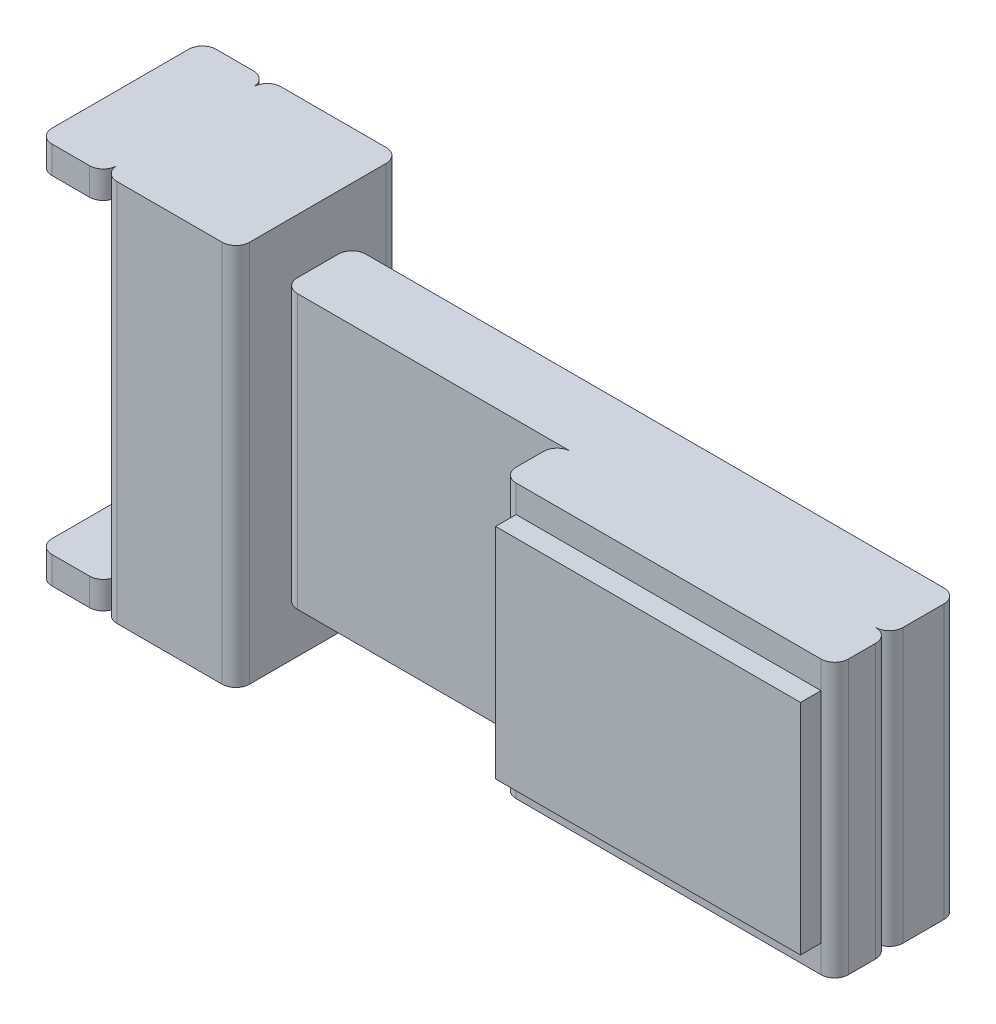
SolidWorks part; units mm, degrees
material "ABS"
ref_plane "Front Plane" through (0, 0, 0) normal (0, 0, 1) x (1, 0, 0)
ref_plane "Top Plane" through (0, 0, 0) normal (0, 1, 0) x (1, 0, 0)
ref_plane "Right Plane" through (0, 0, 0) normal (1, 0, 0) x (0, 0, -1)
sketch "SK_1" plane through (0, 0, 0) normal (0, 1, 0) x (1, 0, 0)
  line L1 (-8.7, -6) -> (-1, -6)
  line L2 (-9.7, -5) -> (-9.7, 5)
  line L3 (-8.7, 6) -> (-1, 6)
  line L4 (0, -5) -> (0, 5)
  line L5 (-9.7, -6) -> (0, 6) construction
  line L6 (-9.7, 6) -> (0, -6) construction
  arc A0 (-1, -6) -> (0, -5) centre (-1, -5) ccw
  arc A1 (-9.7, 5) -> (-8.7, 6) centre (-8.7, 5) cw
  arc A2 (-8.7, -6) -> (-9.7, -5) centre (-8.7, -5) cw
  arc A3 (-1, 6) -> (0, 5) centre (-1, 5) cw
  dimension "D1" = 1
  dimension "W1" = 9.7
  dimension "H1" = 12
  dimension "X1" = 9.7
  dimension "Y1" = 6
extrude "Slider" add sketch "SK_1" along normal blind 28 from offset 14
sketch "SK_2" plane through (0, 0, 0) normal (0, 1, 0) x (1, 0, 0)
  line L1 (-13.45, -6) -> (-10.7, -6)
  line L2 (-14.45, -5) -> (-14.45, 5)
  line L3 (-13.45, 6) -> (-10.7, 6)
  line L4 (-9.7, -5) -> (-9.7, 5)
  line L5 (-14.45, -6) -> (-9.7, 6) construction
  line L6 (-14.45, 6) -> (-9.7, -6) construction
  arc A0 (-10.7, -6) -> (-9.7, -5) centre (-10.7, -5) ccw
  arc A1 (-14.45, 5) -> (-13.45, 6) centre (-13.45, 5) cw
  arc A2 (-13.45, -6) -> (-14.45, -5) centre (-13.45, -5) cw
  arc A3 (-10.7, 6) -> (-9.7, 5) centre (-10.7, 5) cw
  dimension "D1" = 1
  dimension "H1" = 12
  dimension "Y1" = 6
  dimension "W1" = 4.75
  dimension "X1" = 14.45
extrude "Rail_Lip_Top" add sketch "SK_2" along normal blind 2 from offset 12
sketch "SK_3" plane through (0, 0, 0) normal (0, 1, 0) x (1, 0, 0)
  line L1 (-13.45, -6) -> (-10.7, -6)
  line L2 (-14.45, -5) -> (-14.45, 5)
  line L3 (-13.45, 6) -> (-10.7, 6)
  line L4 (-9.7, -5) -> (-9.7, 5)
  line L5 (-14.45, -6) -> (-9.7, 6) construction
  line L6 (-14.45, 6) -> (-9.7, -6) construction
  arc A0 (-10.7, -6) -> (-9.7, -5) centre (-10.7, -5) ccw
  arc A1 (-14.45, 5) -> (-13.45, 6) centre (-13.45, 5) cw
  arc A2 (-13.45, -6) -> (-14.45, -5) centre (-13.45, -5) cw
  arc A3 (-10.7, 6) -> (-9.7, 5) centre (-10.7, 5) cw
  dimension "D1" = 1
  dimension "H1" = 12
  dimension "Y1" = 6
  dimension "W1" = 4.75
  dimension "X1" = 14.45
extrude "Rail_Lip_Bottom" add sketch "SK_3" along normal blind 2 from offset 14
sketch "SK_4" plane through (0, 0, 0) normal (0, 1, 0) x (1, 0, 0)
  line L1 (1, -2.5) -> (43.3, -2.5)
  line L2 (0, -1.5) -> (0, 1.5)
  line L3 (1, 2.5) -> (43.3, 2.5)
  line L4 (44.3, -1.5) -> (44.3, 1.5)
  line L5 (0, -2.5) -> (44.3, 2.5) construction
  line L6 (0, 2.5) -> (44.3, -2.5) construction
  arc A0 (43.3, -2.5) -> (44.3, -1.5) centre (43.3, -1.5) ccw
  arc A1 (0, 1.5) -> (1, 2.5) centre (1, 1.5) cw
  arc A2 (1, -2.5) -> (0, -1.5) centre (1, -1.5) cw
  arc A3 (43.3, 2.5) -> (44.3, 1.5) centre (43.3, 1.5) cw
  dimension "D1" = 1
  dimension "W1" = 44.3
  dimension "H1" = 5
  dimension "Y1" = 2.5
extrude "Finger" add sketch "SK_4" along normal blind 20 from offset 10
sketch "SK_5" plane through (0, 0, 0) normal (0, 1, 0) x (1, 0, 0)
  line L1 (21, -6.5) -> (43.3, -6.5)
  line L2 (20, -5.5) -> (20, -3.5)
  line L3 (21, -2.5) -> (43.3, -2.5)
  line L4 (44.3, -5.5) -> (44.3, -3.5)
  line L5 (20, -6.5) -> (44.3, -2.5) construction
  line L6 (20, -2.5) -> (44.3, -6.5) construction
  arc A0 (43.3, -6.5) -> (44.3, -5.5) centre (43.3, -5.5) ccw
  arc A1 (20, -3.5) -> (21, -2.5) centre (21, -3.5) cw
  arc A2 (21, -6.5) -> (20, -5.5) centre (21, -5.5) cw
  arc A3 (43.3, -2.5) -> (44.3, -3.5) centre (43.3, -3.5) cw
  dimension "D1" = 1
  dimension "W1" = 24.3
  dimension "H1" = 4
  dimension "X1" = 20
  dimension "Y1" = 6.5
extrude "Jaw" add sketch "SK_5" along normal blind 20 from offset 10
sketch "SK_6" plane through (0, 0, 0) normal (0, 1, 0) x (1, 0, 0)
  line L1 (21, -8) -> (43.3, -8)
  line L2 (21, -8) -> (21, -6.5)
  line L3 (21, -6.5) -> (43.3, -6.5)
  line L4 (43.3, -8) -> (43.3, -6.5)
  line L5 (21, -8) -> (43.3, -6.5) construction
  line L6 (21, -6.5) -> (43.3, -8) construction
  dimension "W1" = 22.3
  dimension "H1" = 1.5
  dimension "X1" = 21
  dimension "Y1" = 8
extrude "Grip_Pad" add sketch "SK_6" along normal blind 16 from offset 8
equation "\"Car_L\" = 9.7 'slider block length (rides on the gripper base)"
equation "\"Car_W\" = 12 'slider block width (y)"
equation "\"Fin_L\" = 44.3 'finger length (tip = end_effector_link)"
equation "\"Fin_T\" = 5 'finger thickness (y)"
equation "\"Fin_H\" = 20 'finger height"
equation "\"Rail_T\" = 4.75 'guide rail thickness on link5 (lip length)"
equation "\"Rail_H\" = 24 'guide rail height on link5"
equation "\"Lip_T\" = 2 'lip thickness clamping over the rail"
equation "\"W1@SK_1\" = \"Car_L\""
equation "\"H1@SK_1\" = \"Car_W\""
equation "\"X1@SK_1\" = -((-\"Car_L\"/2)-(\"Car_L\")/2)"
equation "\"Y1@SK_1\" = -((0)-(\"Car_W\")/2)"
equation "\"D1@Slider\" = (\"Rail_H\"/2 + \"Lip_T\")-(-\"Rail_H\"/2 - \"Lip_T\")"
equation "\"D19@Slider\" = -(-\"Rail_H\"/2 - \"Lip_T\")"
equation "\"W1@SK_2\" = \"Rail_T\""
equation "\"H1@SK_2\" = \"Car_W\""
equation "\"X1@SK_2\" = -((-\"Car_L\" - \"Rail_T\"/2)-(\"Rail_T\")/2)"
equation "\"Y1@SK_2\" = -((0)-(\"Car_W\")/2)"
equation "\"D1@Rail_Lip_Top\" = (\"Rail_H\"/2 + \"Lip_T\")-(\"Rail_H\"/2)"
equation "\"D19@Rail_Lip_Top\" = \"Rail_H\"/2"
equation "\"W1@SK_3\" = \"Rail_T\""
equation "\"H1@SK_3\" = \"Car_W\""
equation "\"X1@SK_3\" = -((-\"Car_L\" - \"Rail_T\"/2)-(\"Rail_T\")/2)"
equation "\"Y1@SK_3\" = -((0)-(\"Car_W\")/2)"
equation "\"D1@Rail_Lip_Bottom\" = (-\"Rail_H\"/2)-(-\"Rail_H\"/2 - \"Lip_T\")"
equation "\"D19@Rail_Lip_Bottom\" = -(-\"Rail_H\"/2 - \"Lip_T\")"
equation "\"W1@SK_4\" = \"Fin_L\""
equation "\"H1@SK_4\" = \"Fin_T\""
equation "\"Y1@SK_4\" = -((0)-(\"Fin_T\")/2)"
equation "\"D1@Finger\" = (\"Fin_H\"/2)-(-\"Fin_H\"/2)"
equation "\"D19@Finger\" = -(-\"Fin_H\"/2)"
equation "\"Jaw_X0\" = 20 'jaw start along the finger"
equation "\"Jaw_D\" = 4 'jaw depth towards the object"
equation "\"Pad_T\" = 1.5 'rubber grip pad thickness"
equation "\"Pad_H\" = 16 'rubber grip pad height"
equation "\"W1@SK_5\" = \"Fin_L\" - \"Jaw_X0\""
equation "\"H1@SK_5\" = \"Jaw_D\""
equation "\"X1@SK_5\" = ((\"Jaw_X0\" + \"Fin_L\")/2)-(\"Fin_L\" - \"Jaw_X0\")/2"
equation "\"Y1@SK_5\" = -((-\"Fin_T\"/2 - \"Jaw_D\"/2)-(\"Jaw_D\")/2)"
equation "\"D1@Jaw\" = (\"Fin_H\"/2)-(-\"Fin_H\"/2)"
equation "\"D19@Jaw\" = -(-\"Fin_H\"/2)"
equation "\"W1@SK_6\" = \"Fin_L\" - \"Jaw_X0\" - 2"
equation "\"H1@SK_6\" = \"Pad_T\""
equation "\"X1@SK_6\" = ((\"Jaw_X0\" + \"Fin_L\")/2)-(\"Fin_L\" - \"Jaw_X0\" - 2)/2"
equation "\"Y1@SK_6\" = -((-\"Fin_T\"/2 - \"Jaw_D\" - \"Pad_T\"/2)-(\"Pad_T\")/2)"
equation "\"D1@Grip_Pad\" = (\"Pad_H\"/2)-(-\"Pad_H\"/2)"
equation "\"D19@Grip_Pad\" = -(-\"Pad_H\"/2)"
